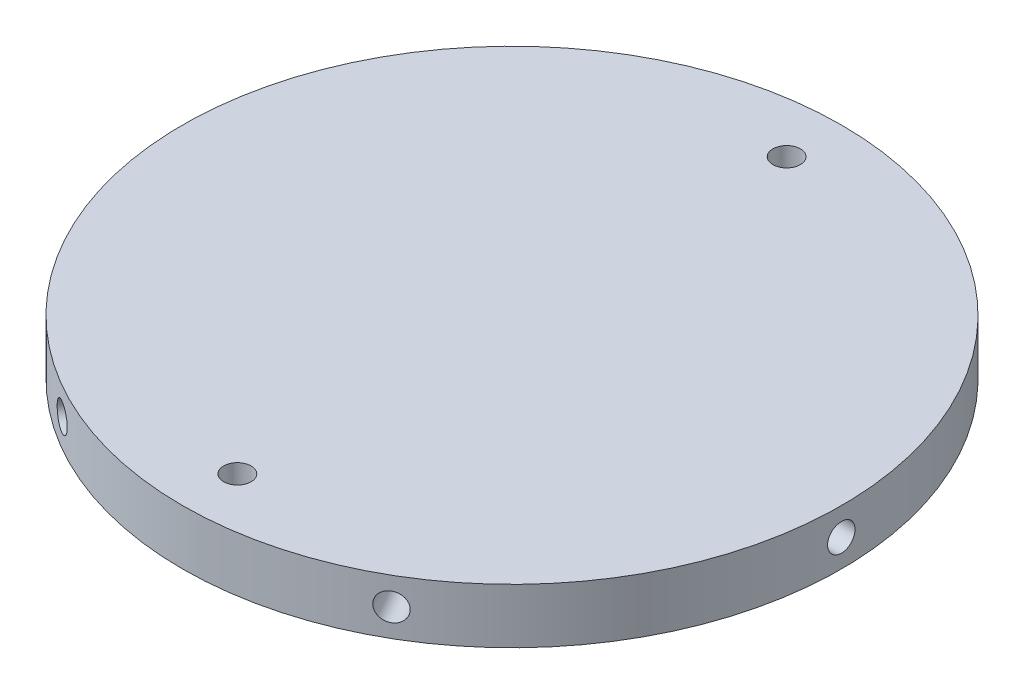
SolidWorks part; units mm, degrees
ref_plane "Front Plane" through (0, 0, 0) normal (0, 0, 1) x (1, 0, 0)
ref_plane "Top Plane" through (0, 0, 0) normal (0, 1, 0) x (1, 0, 0)
ref_plane "Right Plane" through (0, 0, 0) normal (1, 0, 0) x (0, 0, -1)
sketch "Sketch1" plane through (0, 0, 0) normal (0, 1, 0) x (1, 0, 0)
  circle A0 centre (0, 0) radius 76.2
  circle A1 centre (0, -63.5) radius 3.175
  circle A2 centre (0, 63.5) radius 3.175
  dimension "D1" = 63.5
  dimension "D2" = 6.35
  dimension "D3" = 63.5
  dimension "D4" = 6.35
extrude "Boss-Extrude1" add sketch "Sketch1" along normal blind 12.7
ref_plane "Plane1" through (76.2, 0, 0) normal (1, 0, 0) x (0, 0, -1)
sketch "Sketch2" plane through (76.2, 0, 0) normal (1, 0, 0) x (0, 0, -1)
  line L0 (0, 0) -> (0, 12.7) construction
  line L1 (76.2, 12.7) -> (-76.2, 12.7) construction
  circle A0 centre (0, 6.35) radius 3.175
  dimension "D1" = 6.35
extrude "Cut-Extrude1" cut sketch "Sketch2" against normal blind 12.7
pattern_circular "CirPattern1" count 6 over 360 about axis through (0, 0, 0) along (0, 1, 0) of "Cut-Extrude1"
